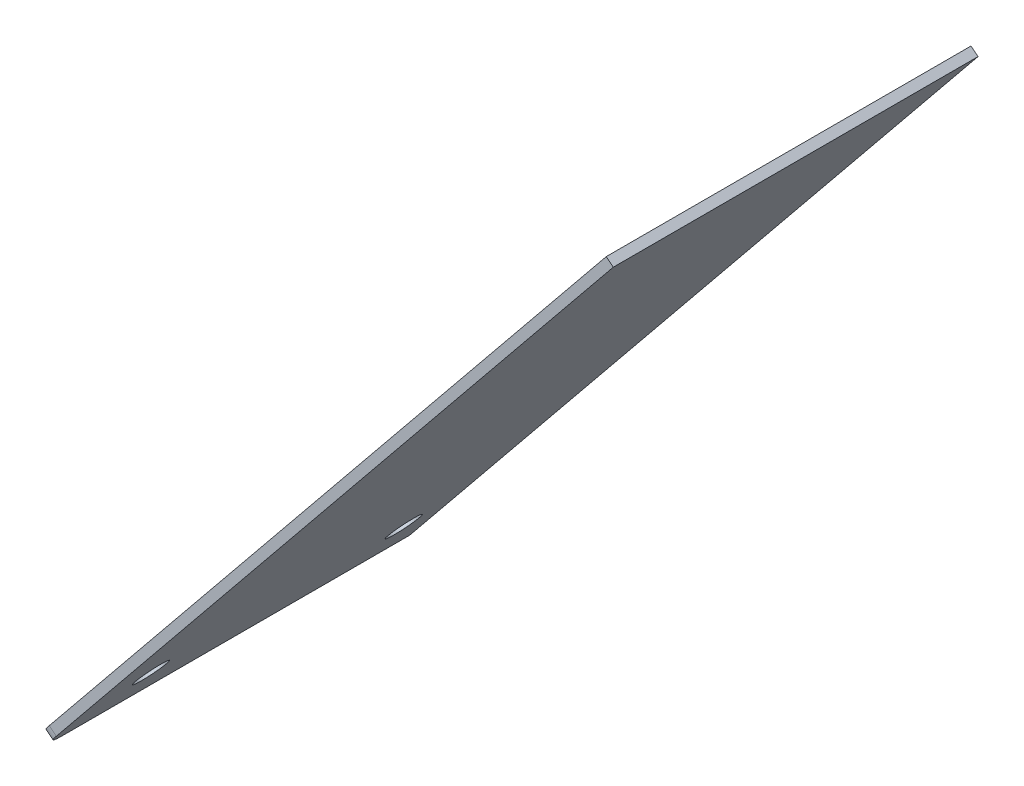
SolidWorks part; units mm, degrees
ref_plane "Front Plane" through (0, 0, 0) normal (0, 0, 1) x (1, 0, 0)
ref_plane "Top Plane" through (0, 0, 0) normal (0, 1, 0) x (1, 0, 0)
ref_plane "Right Plane" through (0, 0, 0) normal (1, 0, 0) x (0, 0, -1)
sketch "Sketch1" plane through (0, 0, 0) normal (0, 0, 1) x (1, 0, 0)
  line L0 (-117.475, -3.175) -> (-615.95, -615.95) construction
  line L1 (-112.549, -7.1821) -> (-117.475, -3.175)
  line L2 (-117.475, -3.175) -> (-517.2676, -494.6397)
  line L3 (-517.2676, -494.6397) -> (-512.3416, -498.6469)
  line L4 (-512.3416, -498.6469) -> (-112.549, -7.1821)
  line L6 (-615.95, -400.4239) -> (-400.4239, -615.95) construction
  circle A0 centre (-615.95, -615.95) radius 77.0255 construction
  point P3 (-519.2711, -497.1027)
  dimension "D1" = 6.35
  dimension "D2" = 3.175
extrude "Boss-Extrude1" add sketch "Sketch1" along normal up to surface (256.54 mm away)
sketch "Sketch2" plane through (-69.1399, 56.2433, 0) normal (-0.7757, 0.631, 0) x (0, 0, 1)
  circle A0 centre (36.195, -659.3342) radius 11.1125 construction
  circle A1 centre (36.195, -659.3342) radius 11.1125
  circle A2 centre (213.995, -659.3342) radius 11.1125 construction
  circle A3 centre (213.995, -659.3342) radius 11.1125
extrude "Cut-Extrude1" cut sketch "Sketch2" against normal up to next
fillet "Fillet1" radius 12.7 1 edges at (-514.8046, -496.6433, 256.54)
